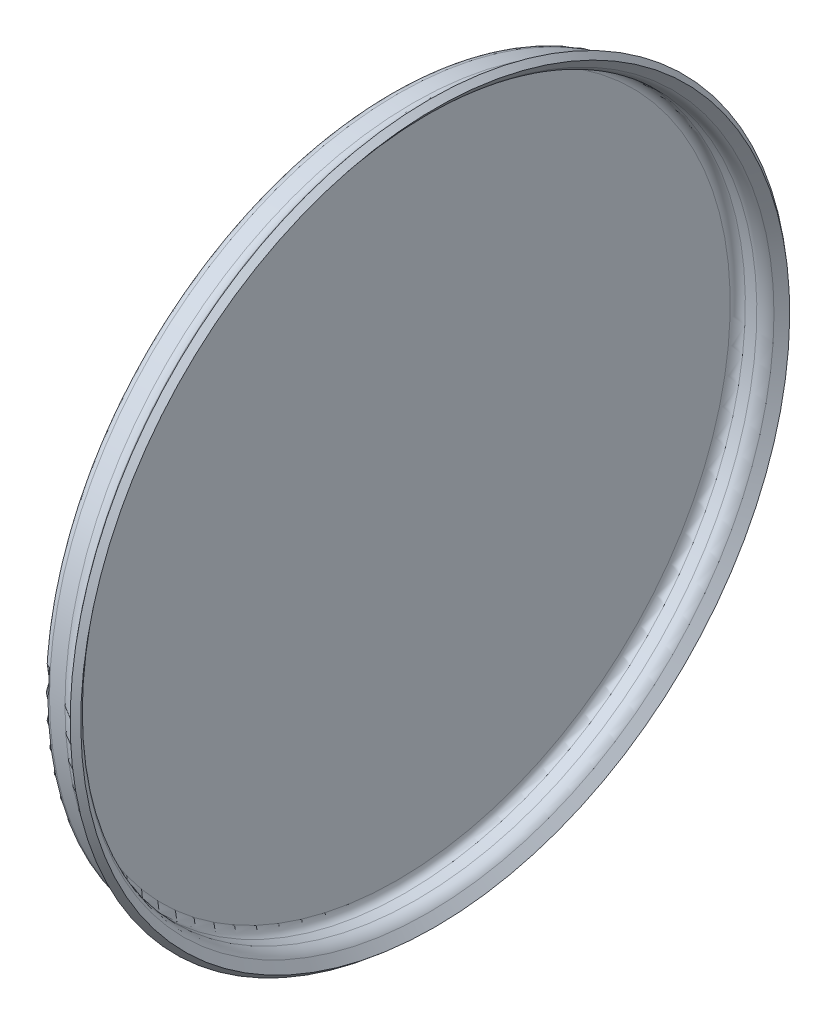
SolidWorks part; units mm, degrees
material "铸造合金钢"
ref_plane "前视基准面" through (0, 0, 0) normal (0, 0, 1) x (1, 0, 0)
ref_plane "上视基准面" through (0, 0, 0) normal (0, 1, 0) x (1, 0, 0)
ref_plane "右视基准面" through (0, 0, 0) normal (1, 0, 0) x (0, 0, -1)
sketch "草图1" plane through (0, 0, 0) normal (0, 0, 1) x (1, 0, 0)
  line L0 (-28.0837, 0) -> (47.5488, 0) construction
  line L1 (-38.0837, -28.5) -> (-32.0837, -28.5)
  line L2 (-30.0837, -30.5) -> (-30.0837, -44)
  line L3 (-29.0837, -45) -> (-27.5655, -45)
  line L4 (-26.0242, -45.7255) -> (-25.0837, -46.8627)
  line L5 (-25.0837, -46.8627) -> (-25.8544, -47.5)
  line L6 (-25.8544, -47.5) -> (-26.4949, -46.7255)
  line L7 (-28.0362, -46) -> (-30.0837, -46)
  line L8 (-31.0837, -45) -> (-31.0837, -31.5)
  line L9 (-33.0837, -29.5) -> (-37.0837, -29.5)
  arc A0 (-38.0837, -28.5) -> (-37.0837, -29.5) centre (-37.0837, -28.5) ccw
  arc A1 (-28.0362, -46) -> (-26.4949, -46.7255) centre (-28.0362, -48) cw
  arc A2 (-27.5655, -45) -> (-26.0242, -45.7255) centre (-27.5655, -47) cw
  arc A3 (-29.0837, -45) -> (-30.0837, -44) centre (-29.0837, -44) cw
  arc A4 (-31.0837, -45) -> (-30.0837, -46) centre (-30.0837, -45) ccw
  arc A5 (-31.0837, -31.5) -> (-33.0837, -29.5) centre (-33.0837, -31.5) ccw
  arc A6 (-30.0837, -30.5) -> (-32.0837, -28.5) centre (-32.0837, -30.5) ccw
  point P20 (-30.0837, -45)
  point P25 (-31.0837, -29.5)
  point P28 (-30.0837, -28.5)
  dimension "D2" = 1
  dimension "D8" = 2
  dimension "D9" = 2
  dimension "D11" = 1
  dimension "D12" = 1
  dimension "D14" = 1
  dimension "D15" = 2
  dimension "D1" = 28.5
  dimension "D4" = 1
  dimension "D6" = 1
  dimension "D7" = 1
  dimension "D10" = 47.5
  dimension "D13" = 10
  dimension "D16" = 6
revolve "旋转1" add sketch "草图1" angle 360 about L0
sketch "草图2" plane through (-31.0837, 0, 0) normal (-1, 0, 0) x (0, 0, 1)
  circle A0 centre (0, 0) radius 36.3664
extrude "切除-拉伸1" cut sketch "草图2" along normal blind 16
sketch "草图3" plane through (-31.0837, 0, 0) normal (-1, 0, 0) x (0, 0, 1)
  circle A0 centre (0, 0) radius 34.4908
extrude "凸台-拉伸1" add sketch "草图3" against normal up to surface (1 mm away) up to face at (-30.0837, -30.5, 0)
